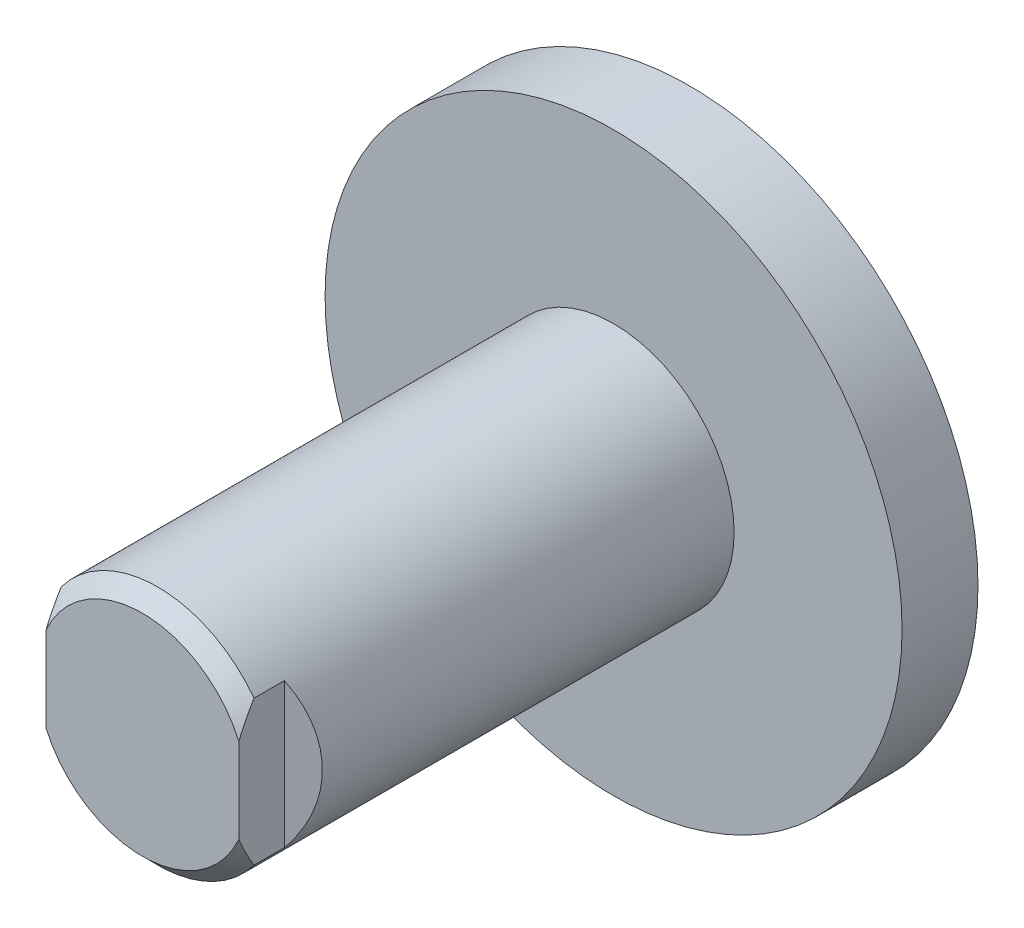
SolidWorks part; units mm, degrees
ref_plane "Front" through (0, 0, 0) normal (0, 0, 1) x (1, 0, 0)
ref_plane "Top" through (0, 0, 0) normal (0, 1, 0) x (1, 0, 0)
ref_plane "Right" through (0, 0, 0) normal (1, 0, 0) x (0, 0, -1)
sketch "Sketch1" plane through (0, 0, 0) normal (0, 0, 1) x (1, 0, 0)
  circle A0 centre (0, 0) radius 19
  dimension "D1" = 38
extrude "Piston" add sketch "Sketch1" along normal blind 5
sketch "Sketch2" plane through (0, 0, 0) normal (0, 0, -1) x (-1, 0, 0)
  circle A0 centre (0, 0) radius 7.9375
  dimension "D1" = 15.875
extrude "Rod" add sketch "Sketch2" against normal up to surface (36.028 mm away)
sketch "Sketch8" plane through (0, 0, 36.028) normal (0, 0, 1) x (1, 0, 0)
  point P0 (0, 0)
hole_wizard "056 #8-32 Internal Thread" [suppressed] positions "3DSketch2" profile "Sketch9" tap size "#8-32" standard "Ansi Inch"
sketch3d "3DSketch2"
  point P0 (0, 0, 19.264)
sketch "Sketch9" plane through (0, 0, 19.264) normal (1, 0, 0) x (0, -1, 0)
  line L0 (0, 0) -> (0, 15.1152)
  line L1 (0, 15.1152) -> (1.7272, 14.0774)
  line L2 (1.7272, 14.0774) -> (1.7272, 11.7)
  line L3 (1.7272, 11.7) -> (2.0828, 11.7)
  line L4 (2.0828, 11.7) -> (2.0828, 0)
  line L5 (2.0828, 0) -> (0, 0)
  line L10 (0, 15.1152) -> (-1.7272, 14.0774) construction
  line L11 (0, -6.35) -> (0, 107.95) construction
  dimension "Tap Drill Dia." = 3.4544
  dimension "Tap Drill Depth" = 14.0774
  dimension "Thread Major Dia." = 4.1656
  dimension "Thread Depth" = 13.2
  dimension "Drill Angle" = 118
hole_wizard "075 #10-32 Internal Thread" [suppressed] positions "3DSketch3" profile "Sketch12" tap size "#10-32" standard "Ansi Inch"
sketch3d "3DSketch3"
  point P0 (0, 0, 74.128)
sketch "Sketch12" plane through (0, 0, 74.128) normal (1, 0, 0) x (0, -1, 0)
  line L0 (0, 0) -> (0, 15.2908)
  line L1 (0, 15.2908) -> (2.0193, 14.0774)
  line L2 (2.0193, 14.0774) -> (2.0193, 11.7)
  line L3 (2.0193, 11.7) -> (2.413, 11.7)
  line L4 (2.413, 11.7) -> (2.413, 0)
  line L5 (2.413, 0) -> (0, 0)
  line L10 (0, 15.2908) -> (-2.0193, 14.0774) construction
  line L11 (0, -6.35) -> (0, 107.95) construction
  dimension "Tap Drill Dia." = 4.0386
  dimension "Tap Drill Depth" = 14.0774
  dimension "Thread Major Dia." = 4.826
  dimension "Thread Depth" = 11.7
  dimension "Drill Angle" = 118
hole_wizard "106 5/16-24 Internal Thread" [suppressed] positions "3DSketch4" profile "Sketch13" tap size "5/16-24" standard "Ansi Inch"
sketch3d "3DSketch4"
  point P0 (0, 0, 31.978)
sketch "Sketch13" plane through (0, 0, 31.978) normal (1, 0, 0) x (0, -1, 0)
  line L0 (0, 0) -> (0, 18.4532)
  line L1 (0, 18.4532) -> (3.4544, 16.3775)
  line L2 (3.4544, 16.3775) -> (3.4544, 13.2)
  line L3 (3.4544, 13.2) -> (3.9687, 13.2)
  line L4 (3.9687, 13.2) -> (3.9687, 0)
  line L5 (3.9687, 0) -> (0, 0)
  line L10 (0, 18.4532) -> (-3.4544, 16.3775) construction
  line L11 (0, -6.35) -> (0, 107.95) construction
  dimension "Tap Drill Dia." = 6.9088
  dimension "Tap Drill Depth" = 16.3775
  dimension "Thread Major Dia." = 7.9375
  dimension "Thread Depth" = 13.2
  dimension "Drill Angle" = 118
hole_wizard "150 3/8-24 Internal Thread" [suppressed] positions "3DSketch5" profile "Sketch14" tap size "3/8-24" standard "Ansi Inch"
sketch3d "3DSketch5"
  point P0 (0, 0, 36.978)
sketch "Sketch14" plane through (0, 0, 36.978) normal (1, 0, 0) x (0, -1, 0)
  line L0 (0, 0) -> (0, 18.411)
  line L1 (0, 18.411) -> (4.2164, 15.8775)
  line L2 (4.2164, 15.8775) -> (4.2164, 12.7)
  line L3 (4.2164, 12.7) -> (4.7625, 12.7)
  line L4 (4.7625, 12.7) -> (4.7625, 0)
  line L5 (4.7625, 0) -> (0, 0)
  line L10 (0, 18.411) -> (-4.2164, 15.8775) construction
  line L11 (0, -6.35) -> (0, 107.95) construction
  dimension "Tap Drill Dia." = 8.4328
  dimension "Tap Drill Depth" = 15.8775
  dimension "Thread Major Dia." = 9.525
  dimension "Thread Depth" = 12.7
  dimension "Drill Angle" = 118
hole_wizard "200-250 1/2-20 Internal Thread" [suppressed] positions "3DSketch6" profile "Sketch15" tap size "1/2-20" standard "Ansi Inch"
sketch3d "3DSketch6"
  point P0 (0, 0, 50.915)
sketch "Sketch15" plane through (0, 0, 50.915) normal (1, 0, 0) x (0, -1, 0)
  line L0 (0, 0) -> (0, 18.4676)
  line L1 (0, 18.4676) -> (5.7544, 15.01)
  line L2 (5.7544, 15.01) -> (5.7544, 11.2)
  line L3 (5.7544, 11.2) -> (6.35, 11.2)
  line L4 (6.35, 11.2) -> (6.35, 0)
  line L5 (6.35, 0) -> (0, 0)
  line L10 (0, 18.4676) -> (-5.7544, 15.01) construction
  line L11 (0, -6.35) -> (0, 107.95) construction
  dimension "Tap Drill Dia." = 11.5087
  dimension "Tap Drill Depth" = 15.01
  dimension "Thread Major Dia." = 12.7
  dimension "Thread Depth" = 11.2
  dimension "Drill Angle" = 118
chamfer "Rod End Chamfer" distance 1 angle 45 1 edges at (-7.9375, 0, 36.028)
sketch "Sketch11" plane through (0, 0, 0) normal (0, 1, 0) x (1, 0, 0)
  line L0 (0, -36.028) -> (0, -54.2319) construction
  line L1 (-6.35, -36.028) -> (-6.35, -33.028)
  line L2 (6.35, -36.028) -> (6.35, -33.028)
  line L3 (-6.35, -33.028) -> (-11.35, -30.1412)
  line L4 (6.35, -33.028) -> (11.35, -30.1412)
  line L5 (-11.35, -30.1412) -> (-11.35, -36.028)
  line L6 (11.35, -30.1412) -> (11.35, -36.028)
  line L7 (-11.35, -36.028) -> (-6.35, -36.028)
  line L8 (11.35, -36.028) -> (6.35, -36.028)
  line L9 (-7.9375, -36.028) -> (7.9375, -36.028) construction
  dimension "D1" = 60
  dimension "D2" = 5
  dimension "D3" = 3
  dimension "D4" = 12.7
extrude "Wrench Flats" cut sketch "Sketch11" against normal through all and the other way through all
sketch "Sketch16" plane through (0, 0, 36.028) normal (0, 0, 1) x (1, 0, 0)
  circle A0 centre (0, 0) radius 2.0828
  dimension "D1" = 4.1656
extrude "External Thread" [suppressed] add sketch "Sketch16" along normal blind 9.652
chamfer "External Rod Thread Chamfer" [suppressed] distance 0.2 angle 45
